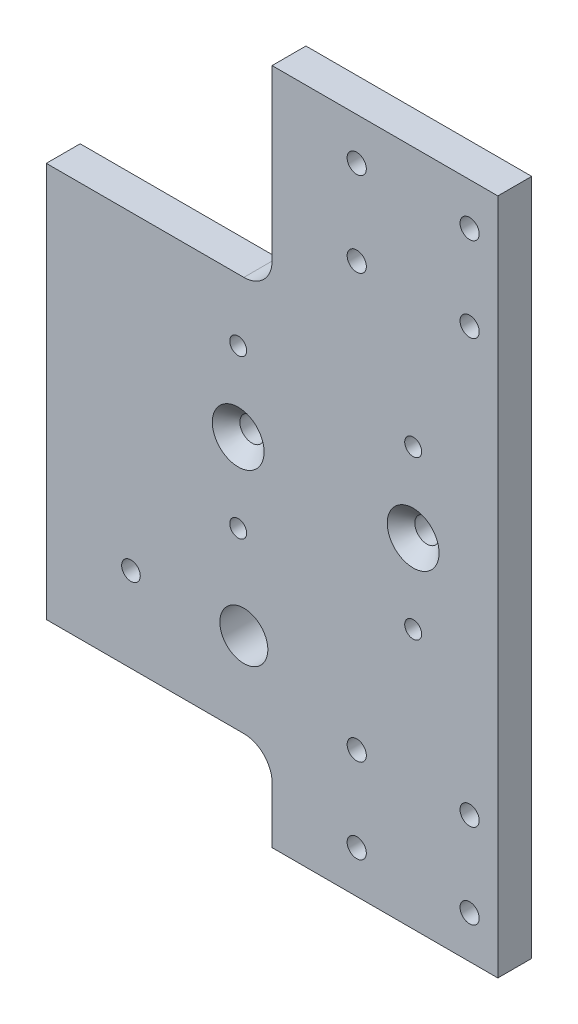
SolidWorks part; units mm, degrees
ref_plane "Front Plane" through (0, 0, 0) normal (0, 0, 1) x (1, 0, 0)
ref_plane "Top Plane" through (0, 0, 0) normal (0, 1, 0) x (1, 0, 0)
ref_plane "Right Plane" through (0, 0, 0) normal (1, 0, 0) x (0, 0, -1)
ref_plane "Ebene1" through (0, 0, 10) normal (0, 0, 1) x (1, 0, 0)
sketch "Skizze1" plane through (0, 0, 10) normal (0, 0, 1) x (1, 0, 0)
  line L0 (-80, 120) -> (0, 120)
  line L1 (-80, 120) -> (-80, 0)
  line L4 (-80, 0) -> (0, 0)
  line L5 (0, 0) -> (0, 120)
  line L6 (-80, 60) -> (0, 60) construction
  dimension "D1" = 120
  dimension "D2" = 80
extrude "Aufsatz-Linear austragen1" add sketch "Skizze1" against normal blind 6
hole_wizard "Formsenkung für M4 Senkschraube mit Innensechskant1" positions "Skizze18" profile "Skizze19" countersink size "M4" standard "DIN"
sketch "Skizze18" plane through (0, 0, 10) normal (0, 0, 1) x (1, 0, 0)
  line L0 (-80, 60) -> (0, 60) construction
  line L3 (0, 0) -> (0, 120) construction
  line L4 (-80, 120) -> (-80, 0) construction
  point P0 (-46, 60)
  point P3 (-15, 60)
  dimension "D1" = 31
  dimension "D2" = 15
sketch "Skizze19" plane through (-46, 60, 10) normal (1, 0, 0) x (0, -1, 0)
  line L0 (0, 0) -> (0, 12.7919)
  line L1 (0, 12.7919) -> (2.15, 11.5)
  line L2 (2.15, 11.5) -> (2.15, 2.44)
  line L3 (2.15, 2.44) -> (4.59, 0)
  line L5 (4.59, 0) -> (0, 0)
  line L6 (-2.15, 2.44) -> (-4.59, 0) construction
  line L10 (0, 12.7919) -> (-2.15, 11.5) construction
  line L11 (0, -6.35) -> (0, 107.95) construction
  dimension "Bohrerdurchmesser" = 4.3
  dimension "Bohrungstiefe" = 11.5
  dimension "Senkdurchmesser (Oben)" = 9.18
  dimension "Senkwinkel (Oben)" = 90
  dimension "Spitzenwinkel" = 118
hole_wizard "Ø3.0mm Stiftloch1" positions "Skizze20" profile "Skizze21" hole size "Ø3.0" standard "DIN"
sketch "Skizze20" plane through (0, 0, 10) normal (0, 0, 1) x (1, 0, 0)
  line L0 (-46, 60) -> (-46, 74) construction
  line L3 (-15, 60) -> (-15, 74) construction
  line L4 (-46, 60) -> (-15, 60) construction
  line L6 (-46, 74) -> (-15, 74) construction
  point P0 (-46, 74)
  point P18 (-15, 74)
  point P26 (-15, 46)
  point P27 (-46, 46)
  dimension "D1" = 28
sketch "Skizze21" plane through (-46, 74, 10) normal (1, 0, 0) x (0, -1, 0)
  line L0 (0, 0) -> (0, 12.4013)
  line L1 (0, 12.4013) -> (1.5, 11.5)
  line L2 (1.5, 11.5) -> (1.5, 0)
  line L5 (1.5, 0) -> (0, 0)
  line L10 (0, 12.4013) -> (-1.5, 11.5) construction
  line L11 (0, -6.35) -> (0, 107.95) construction
  dimension "Bohrerdurchmesser" = 3
  dimension "Bohrungstiefe" = 11.5
  dimension "Spitzenwinkel" = 118
hole_wizard "Stirnsenkung für M3 Flachkopfschraube mit Schlitz2" positions "Skizze24" profile "Skizze25" counterbore size "M3" standard "DIN"
sketch "Skizze24" plane through (0, 0, 4) normal (0, 0, -1) x (-1, 0, 0)
  line L0 (25, 112.5) -> (25, 97.5) construction
  line L1 (0, 120) -> (80, 120) construction
  line L2 (80, 0) -> (0, 0) construction
  line L3 (15, 120) -> (15, 0) construction
  line L7 (80, 60) -> (0, 60) construction
  line L8 (80, 120) -> (80, 0) construction
  line L9 (0, 0) -> (0, 120) construction
  point P0 (25, 112.5)
  point P12 (25, 97.5)
  point P23 (5, 97.5)
  point P24 (5, 112.5)
  point P34 (25, 22.5)
  point P35 (25, 7.5)
  point P36 (5, 7.5)
  point P37 (5, 22.5)
  dimension "D1" = 15
  dimension "D2" = 20
  dimension "D3" = 15
  dimension "D5" = 90
  dimension "D4" = 2
sketch "Skizze25" plane through (-25, 112.5, 4) normal (1, 0, 0) x (0, 1, 0)
  line L0 (0, 0) -> (0, 9.5215)
  line L1 (0, 9.5215) -> (1.7, 8.5)
  line L2 (1.7, 8.5) -> (1.7, 2.4)
  line L3 (1.7, 2.4) -> (3.5, 2.4)
  line L4 (3.5, 2.4) -> (3.5, 0)
  line L5 (3.5, 0) -> (0, 0)
  line L10 (0, 9.5215) -> (-1.7, 8.5) construction
  line L11 (0, -6.35) -> (0, 107.95) construction
  dimension "Bohrerdurchmesser" = 3.4
  dimension "Bohrungstiefe" = 8.5
  dimension "Senkdurchmesser2" = 7
  dimension "Senktiefe2" = 2.4
  dimension "Spitzenwinkel" = 118
hole_wizard "M10 Gewindebohrung1" positions "Skizze26" profile "Skizze27" tap size "M10" standard "DIN" end condition through all
sketch "Skizze26" plane through (0, 0, 4) normal (0, 0, -1) x (-1, 0, 0)
  line L0 (45, 0) -> (45, 120) construction
  line L1 (80, 0) -> (0, 0) construction
  line L2 (0, 120) -> (80, 120) construction
  line L4 (0, 0) -> (0, 120) construction
  line L5 (0, 60) -> (80, 60) construction
  line L6 (80, 120) -> (80, 0) construction
  point P0 (45, 30)
  dimension "D1" = 45
  dimension "D2" = 30
sketch "Skizze27" plane through (-45, 30, 4) normal (1, 0, 0) x (0, 1, 0)
  line L0 (0, 0) -> (0, 6)
  line L1 (0, 6) -> (4.25, 6)
  line L2 (4.25, 6) -> (4.25, 0)
  line L5 (4.25, 0) -> (0, 0)
  line L11 (0, -6.35) -> (0, 107.95) construction
  dimension "Bohrerdurchmesser" = 8.5
  dimension "Bohrungstiefe" = 6
cosmetic thread "Bohrungsgewinde1" parameters "D2"=10
sketch "Skizze28" plane through (0, 0, 4) normal (0, 0, -1) x (-1, 0, 0)
  line L1 (80, 120) -> (40, 120)
  line L2 (80, 120) -> (80, 85)
  line L3 (80, 85) -> (40, 85)
  line L4 (40, 120) -> (40, 85)
  line L5 (60, 85) -> (60, 120) construction
  line L6 (80, 102.5) -> (40, 102.5) construction
  line L7 (80, 0) -> (40, 0)
  line L8 (80, 0) -> (80, 15)
  line L9 (80, 15) -> (40, 15)
  line L10 (40, 0) -> (40, 15)
  line L11 (60, 15) -> (60, 0) construction
  line L12 (80, 7.5) -> (40, 7.5) construction
  point P204 (60, 102.5)
  point P430 (60, 7.5)
  dimension "D1" = 40
  dimension "D2" = 40
  dimension "D3" = 15
  dimension "D4" = 35
extrude "Schnitt-Linear austragen1" cut sketch "Skizze28" against normal blind 10
hole_wizard "M4 Gewindebohrung1" positions "Skizze29" profile "Skizze30" tap size "M4" standard "DIN" end condition through all
sketch "Skizze29" plane through (0, 0, 4) normal (0, 0, -1) x (-1, 0, 0)
  line L0 (80, 15) -> (40, 15) construction
  line L1 (80, 85) -> (80, 15) construction
  point P0 (65, 30)
  dimension "D1" = 15
  dimension "D2" = 15
sketch "Skizze30" plane through (-65, 30, 4) normal (1, 0, 0) x (0, 1, 0)
  line L0 (0, 0) -> (0, 6)
  line L1 (0, 6) -> (1.65, 6)
  line L2 (1.65, 6) -> (1.65, 0.375)
  line L3 (1.65, 0.375) -> (2.025, 0)
  line L5 (2.025, 0) -> (0, 0)
  line L6 (-1.65, 0.375) -> (-2.025, 0) construction
  line L11 (0, -6.35) -> (0, 107.95) construction
  dimension "Bohrerdurchmesser" = 3.3
  dimension "Bohrungstiefe" = 6
  dimension "Senkdurchmesser (Oben)" = 4.05
  dimension "Senkwinkel (Oben)" = 90
cosmetic thread "Bohrungsgewinde2" parameters "D2"=4
fillet "Verrundung1" radius 5 2 edges at (-40, 85, 7) (-40, 15, 7)
